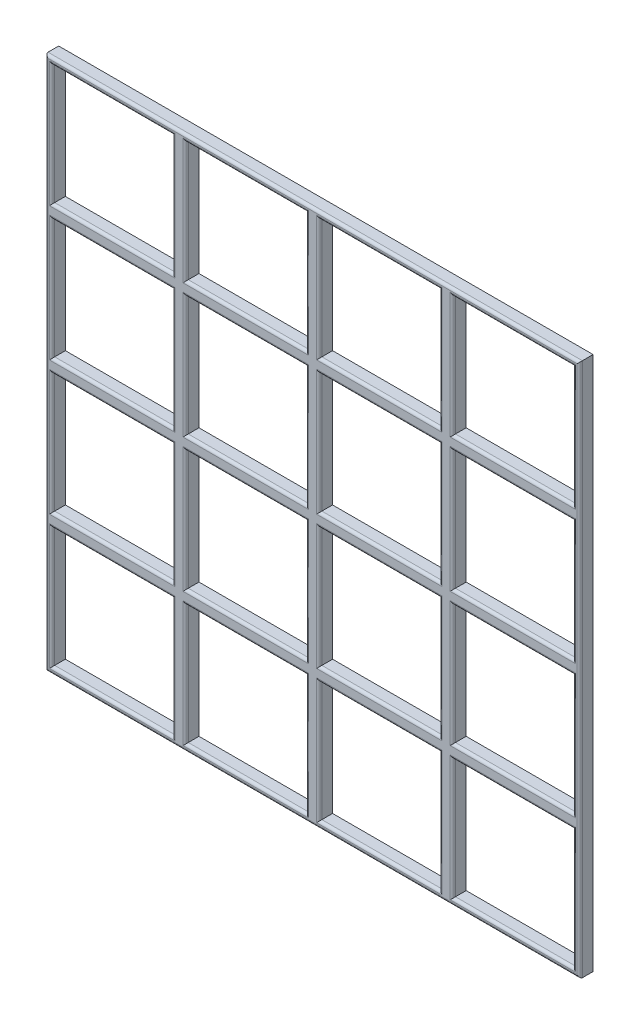
SolidWorks part; units mm, degrees
ref_plane "Front Plane" through (0, 0, 0) normal (0, 0, 1) x (1, 0, 0)
ref_plane "Top Plane" through (0, 0, 0) normal (0, 1, 0) x (1, 0, 0)
ref_plane "Right Plane" through (0, 0, 0) normal (1, 0, 0) x (0, 0, -1)
sketch "Sketch2" plane through (0, 0, 0) normal (0, 0, 1) x (1, 0, 0)
  line L0 (-47.5, -97.5) -> (-2.5, -97.5)
  line L1 (-100, -100) -> (100, -100)
  line L2 (-100, -100) -> (-100, 100)
  line L3 (-100, 100) -> (100, 100)
  line L4 (100, -100) -> (100, 100)
  line L5 (-97.5, 52.5) -> (-52.5, 52.5)
  line L6 (-52.5, 97.5) -> (-52.5, 52.5)
  line L11 (-98.75, -98.75) -> (100, 100) construction
  line L12 (-98.75, 98.75) -> (98.75, -98.75) construction
  line L13 (-97.5, -97.5) -> (-52.5, -97.5)
  line L14 (-97.5, -97.5) -> (-97.5, -52.5)
  line L17 (-97.5, -97.5) -> (-52.5, -52.5) construction
  line L18 (-97.5, -52.5) -> (-52.5, -97.5) construction
  line L22 (-47.5, -97.5) -> (-2.5, -52.5) construction
  line L23 (-47.5, -52.5) -> (-2.5, -97.5) construction
  line L24 (2.5, -97.5) -> (47.5, -97.5)
  line L28 (2.5, -97.5) -> (47.5, -52.5) construction
  line L29 (2.5, -52.5) -> (47.5, -97.5) construction
  line L30 (52.5, -97.5) -> (97.5, -97.5)
  line L33 (97.5, -97.5) -> (97.5, -52.5)
  line L34 (52.5, -97.5) -> (97.5, -52.5) construction
  line L35 (52.5, -52.5) -> (97.5, -97.5) construction
  line L40 (-47.5, -47.5) -> (-2.5, -2.5) construction
  line L41 (-47.5, -2.5) -> (-2.5, -47.5) construction
  line L46 (-47.5, 97.5) -> (-47.5, 52.5)
  line L47 (-2.5, 97.5) -> (-2.5, 52.5)
  line L51 (97.5, -47.5) -> (97.5, -2.5)
  line L52 (52.5, -47.5) -> (97.5, -2.5) construction
  line L53 (52.5, -2.5) -> (97.5, -47.5) construction
  line L58 (-47.5, 2.5) -> (2.5, 52.5) construction
  line L59 (-47.5, 47.5) -> (-2.5, 2.5) construction
  line L64 (2.5, 2.5) -> (47.5, 47.5) construction
  line L65 (2.5, 47.5) -> (47.5, 2.5) construction
  line L69 (97.5, 2.5) -> (97.5, 47.5)
  line L70 (52.5, 2.5) -> (97.5, 47.5) construction
  line L71 (52.5, 47.5) -> (97.5, 2.5) construction
  line L74 (-47.5, 97.5) -> (-2.5, 97.5)
  line L76 (-47.5, 52.5) -> (-2.5, 97.5) construction
  line L77 (-47.5, 97.5) -> (-2.5, 52.5) construction
  line L80 (2.5, 97.5) -> (47.5, 97.5)
  line L82 (2.5, 52.5) -> (47.5, 97.5) construction
  line L83 (2.5, 97.5) -> (47.5, 52.5) construction
  line L86 (52.5, 97.5) -> (97.5, 97.5)
  line L87 (97.5, 52.5) -> (97.5, 97.5)
  line L88 (52.5, 52.5) -> (97.5, 97.5) construction
  line L89 (52.5, 97.5) -> (97.5, 52.5) construction
  line L91 (-97.5, -47.5) -> (-97.5, -2.5)
  line L94 (-97.5, -47.5) -> (-52.5, -2.5) construction
  line L95 (-97.5, -2.5) -> (-52.5, -47.5) construction
  line L97 (-97.5, 2.5) -> (-97.5, 47.5)
  line L100 (-97.5, 2.5) -> (-52.5, 47.5) construction
  line L101 (-97.5, 47.5) -> (-52.5, 2.5) construction
  line L103 (-97.5, 52.5) -> (-97.5, 97.5)
  line L104 (-97.5, 97.5) -> (-52.5, 97.5)
  line L106 (-97.5, 52.5) -> (-52.5, 97.5) construction
  line L107 (-97.5, 97.5) -> (-52.5, 52.5) construction
  line L108 (2.5, 97.5) -> (2.5, 52.5)
  line L109 (47.5, 97.5) -> (47.5, 52.5)
  line L110 (-47.5, 2.5) -> (-2.5, 2.5) [skipped]
  line L113 (2.5, 2.5) -> (47.5, 2.5) [skipped]
  line L115 (52.5, 2.5) -> (52.5, 47.5) [skipped]
  line L116 (52.5, -47.5) -> (52.5, -2.5) [skipped]
  line L118 (2.5, -47.5) -> (47.5, -47.5) [skipped]
  line L119 (-47.5, -47.5) -> (-2.5, -47.5) [skipped]
  line L120 (-47.5, -47.5) -> (-47.5, -2.5) [skipped]
  line L122 (-47.5, 2.5) -> (-47.5, 47.5) [skipped]
  line L127 (2.5, 2.5) -> (2.5, 47.5) [skipped]
  line L128 (2.5, -47.5) -> (2.5, -2.5) [skipped]
  line L131 (-47.5, 52.5) -> (-2.5, 52.5) [skipped]
  line L132 (2.5, 52.5) -> (47.5, 52.5) [skipped]
  line L134 (2.5, -47.5) -> (47.5, -2.5) construction
  line L135 (2.5, -2.5) -> (47.5, -47.5) construction
  line L136 (-97.5, 52.5) -> (-53.5607, 52.5) [skipped]
  line L138 (53.5607, 52.5) -> (97.5, 52.5) [skipped]
  line L139 (-47.5, 58.0409) -> (-47.5, 97.5) [skipped]
  line L141 (2.5, 52.5) -> (2.5, 97.5) [skipped]
  line L143 (52.5, 53.5607) -> (52.5, 97.5) [skipped]
  line L144 (52.5, -97.5) -> (52.5, -53.5607) [skipped]
  line L147 (-97.5, 2.5) -> (-74.9583, 2.5) [skipped]
  line L150 (74.9583, 2.5) -> (97.5, 2.5) [skipped]
  line L152 (58.0409, -47.5) -> (97.5, -47.5) [skipped]
  line L154 (2.5, -97.5) -> (2.5, -74.9583) [skipped]
  line L156 (-47.5, -97.5) -> (-47.5, -58.0409) [skipped]
  line L157 (-97.5, -47.5) -> (-58.0409, -47.5) [skipped]
  line L158 (52.5, 97.5) -> (52.5, 52.5)
  line L159 (-97.5, 47.5) -> (-52.5, 47.5)
  line L160 (-97.5, 2.5) -> (-52.5, 2.5)
  line L161 (97.5, -2.5) -> (52.5, -2.5)
  line L162 (-97.5, -47.5) -> (-52.5, -47.5)
  line L163 (-97.5, -52.5) -> (-52.5, -52.5)
  line L164 (52.5, -47.5) -> (97.5, -47.5)
  line L165 (52.5, -52.5) -> (52.5, -97.5)
  line L166 (52.5, -52.5) -> (97.5, -52.5)
  line L167 (47.5, -52.5) -> (47.5, -97.5)
  line L168 (2.5, -47.5) -> (47.5, -47.5)
  line L169 (2.5, -52.5) -> (2.5, -97.5)
  line L170 (2.5, -52.5) -> (47.5, -52.5)
  line L171 (-2.5, -52.5) -> (-2.5, -97.5)
  line L172 (-47.5, -52.5) -> (-47.5, -97.5)
  line L173 (-47.5, -52.5) -> (-2.5, -52.5)
  line L174 (-47.5, -47.5) -> (-2.5, -47.5)
  line L175 (-52.5, -52.5) -> (-52.5, -97.5)
  line L176 (-52.5, -2.5) -> (-97.5, -2.5)
  line L177 (-47.5, 2.5) -> (-2.5, 2.5)
  line L178 (-47.5, -2.5) -> (-47.5, -47.5)
  line L179 (-52.5, -2.5) -> (-52.5, -47.5)
  line L180 (2.5, 2.5) -> (47.5, 2.5)
  line L181 (2.5, -2.5) -> (2.5, -47.5)
  line L182 (-2.5, -2.5) -> (-47.5, -2.5)
  line L183 (-2.5, -2.5) -> (-2.5, -47.5)
  line L184 (47.5, -2.5) -> (47.5, -47.5)
  line L185 (52.5, 2.5) -> (97.5, 2.5)
  line L186 (52.5, -2.5) -> (52.5, -47.5)
  line L187 (47.5, -2.5) -> (2.5, -2.5)
  line L188 (52.5, 52.5) -> (97.5, 52.5)
  line L189 (52.5, 47.5) -> (97.5, 47.5)
  line L190 (52.5, 47.5) -> (52.5, 2.5)
  line L191 (47.5, 47.5) -> (47.5, 2.5)
  line L192 (2.5, 52.5) -> (47.5, 52.5)
  line L193 (-2.5, 47.5) -> (-2.5, 2.5)
  line L194 (2.5, 47.5) -> (47.5, 47.5)
  line L195 (2.5, 47.5) -> (2.5, 2.5)
  line L196 (-52.5, 47.5) -> (-52.5, 2.5)
  line L197 (-47.5, 52.5) -> (-2.5, 52.5)
  line L198 (-47.5, 47.5) -> (-47.5, 2.5)
  line L199 (-47.5, 47.5) -> (-2.5, 47.5)
  point P11 (-75, -75)
  point P18 (-25, -75)
  point P23 (25, -75)
  point P28 (75, -75)
  point P38 (-25, -25)
  point P39 (25, 25)
  point P40 (-25, 25)
  point P41 (25, -25)
  point P43 (75, -25)
  point P58 (75, 25)
  point P63 (-25, 75)
  point P68 (25, 75)
  point P73 (75, 75)
  point P78 (-75, -25)
  point P83 (-75, 25)
  point P88 (-75, 75)
  dimension "D1" = 200
  dimension "D2" = 4
  dimension "D3" = 4
  dimension "D4" = 200
extrude "Boss-Extrude1" add sketch "Sketch2" along normal blind 5
fillet "Fillet2" radius 1 68 edges at (-75, 97.5, 5) (-97.5, 75, 5) (-97.5, -25, 5) (25, 97.5, 5) (97.5, 25, 5) (75, -97.5, 5) (97.5, -75, 5) (-25, -97.5, 5) (0, -100, 5) (-100, 0, 5) (0, 100, 5) (100, 0, 5) (-97.5, -75, 5) (-75, -97.5, 5) (25, -97.5, 5) (97.5, -25, 5) (-25, 97.5, 5) (75, 97.5, 5) (97.5, 75, 5) (-97.5, 25, 5) (-75, 52.5, 5) (-52.5, 75, 5) (-75, -2.5, 5) (-75, -47.5, 5) (-52.5, -25, 5) (2.5, 75, 5) (25, 52.5, 5) (47.5, 75, 5) (52.5, 25, 5) (75, 2.5, 5) (75, 47.5, 5) (52.5, -25, 5) (75, -47.5, 5) (75, -2.5, 5) (52.5, -75, 5) (75, -52.5, 5) (-47.5, -75, 5) (-2.5, -75, 5) (-25, -52.5, 5) (-75, -52.5, 5) (-52.5, -75, 5) (25, -2.5, 5) (2.5, -25, 5) (25, -47.5, 5) (47.5, -25, 5) (-47.5, 25, 5) (-25, 2.5, 5) (-2.5, 25, 5) (-25, 47.5, 5) (2.5, -75, 5) (47.5, -75, 5) (25, -52.5, 5) (-25, -2.5, 5) (-47.5, -25, 5) (-25, -47.5, 5) (-2.5, -25, 5) (2.5, 25, 5) (25, 2.5, 5) (47.5, 25, 5) (25, 47.5, 5) (-47.5, 75, 5) (-25, 52.5, 5) (-2.5, 75, 5) (52.5, 75, 5) (75, 52.5, 5) (-75, 47.5, 5) (-75, 2.5, 5) (-52.5, 25, 5)
